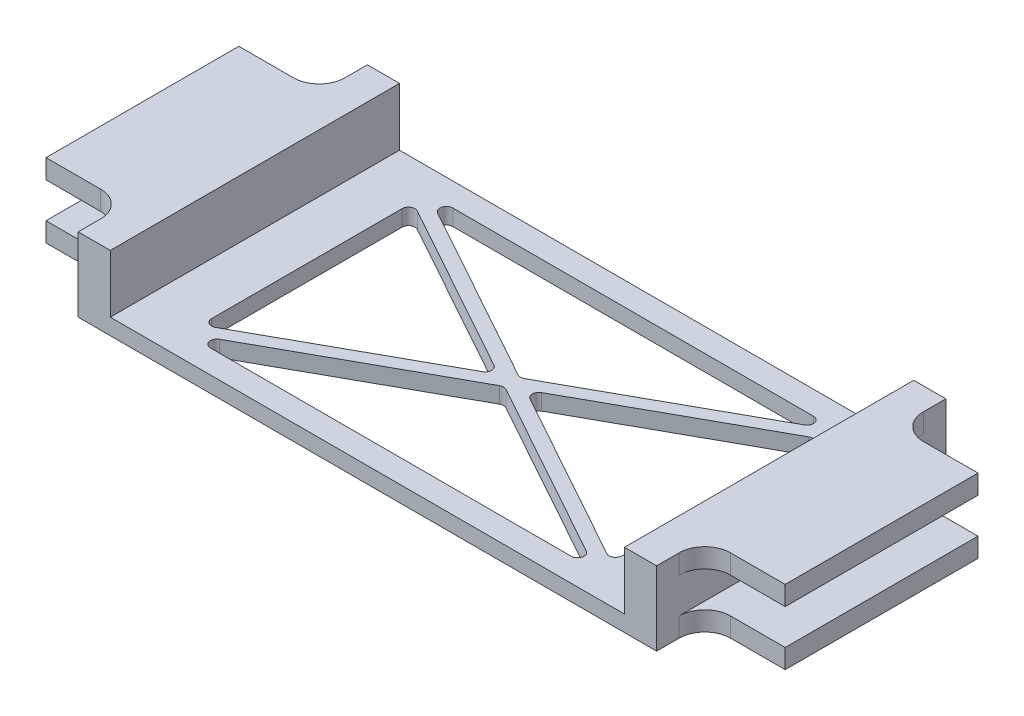
SolidWorks part; units mm, degrees
ref_plane "Front Plane" through (0, 0, 0) normal (0, 0, 1) x (1, 0, 0)
ref_plane "Top Plane" through (0, 0, 0) normal (0, 1, 0) x (1, 0, 0)
ref_plane "Right Plane" through (0, 0, 0) normal (1, 0, 0) x (0, 0, -1)
sketch "Sketch1" plane through (0, 0, 0) normal (0, 1, 0) x (1, 0, 0)
  line L1 (57.5, -15) -> (-57.5, -15)
  line L2 (57.5, -15) -> (57.5, 15)
  line L3 (57.5, 15) -> (-57.5, 15)
  line L4 (-57.5, -15) -> (-57.5, 15)
  line L5 (57.5, -15) -> (-57.5, 15) construction
  line L6 (57.5, 15) -> (-57.5, -15) construction
  line L7 (45, -22.5) -> (-45, -22.5)
  line L8 (45, -22.5) -> (45, 22.5)
  line L9 (45, 22.5) -> (-45, 22.5)
  line L10 (-45, -22.5) -> (-45, 22.5)
  line L11 (45, -22.5) -> (-45, 22.5) construction
  line L12 (45, 22.5) -> (-45, -22.5) construction
  point P0 (0, 0)
  point P6 (0, 0)
  dimension "D1" = 30
  dimension "D2" = 115
  dimension "D3" = 45
  dimension "D4" = 90
extrude "Boss-Extrude1" add sketch "Sketch1" along normal blind 11.5 contours L1 L10 L3 L4 | L10 L3 L8 L9 | L10 L1 L8 L3 | L10 L7 L8 L1 | L8 L1 L2 L3
sketch "Sketch2" plane through (0, 0, 15) normal (0, 0, 1) x (1, 0, 0)
  line L0 (-45, 11.5) -> (-45, 0) construction
  line L1 (-32.5, 3) -> (-57.5, 3)
  line L2 (-32.5, 3) -> (-32.5, 8.5)
  line L3 (-32.5, 8.5) -> (-57.5, 8.5)
  line L4 (-57.5, 3) -> (-57.5, 8.5)
  line L5 (-32.5, 3) -> (-57.5, 8.5) construction
  line L6 (-32.5, 8.5) -> (-57.5, 3) construction
  line L7 (-57.5, 11.5) -> (-57.5, 0) construction
  line L8 (-45, 11.5) -> (-57.5, 11.5) construction
  line L10 (-45, 3) -> (-45, 8.5)
  point P0 (-45, 5.75)
  line M4 (-45, 0) -> (-45, 11.5)
  line M6 (-57.5, 11.5) -> (-57.5, 0)
  dimension "D1" = 3
extrude "Cut-Extrude1" cut sketch "Sketch2" against normal through all contours L3 L1 M4 M6
mirror "Mirror1" about plane through (0, 0, 0) normal (1, 0, 0) of "Cut-Extrude1"
sketch "Sketch3" plane through (0, 0, 22.5) normal (0, 0, 1) x (1, 0, 0)
  line L0 (45, 11.5) -> (-45, 11.5) construction
  line L1 (-40, 11.5) -> (40, 11.5)
  line L2 (-40, 11.5) -> (-40, 2.5)
  line L3 (-40, 2.5) -> (40, 2.5)
  line L4 (40, 11.5) -> (40, 2.5)
  line L5 (-45, 11.5) -> (-45, 0) construction
  line L7 (45, 11.5) -> (45, 0) construction
  dimension "D1" = 5
  dimension "D2" = 5
  dimension "D3" = 9
extrude "Cut-Extrude2" cut sketch "Sketch3" against normal through all both and the other way through all
fillet "Fillet1" radius 4 8 edges at (45, 1.5, -15) (45, 10, -15) (45, 1.5, 15) (45, 10, 15) (-45, 1.5, -15) (-45, 10, -15) (-45, 1.5, 15) (-45, 10, 15)
sketch "Sketch4" plane through (0, 0, 0) normal (0, -1, 0) x (1, 0, 0)
  line L0 (45, 22.5) -> (-45, 22.5) construction
  line L1 (40, -22.5) -> (-40, -22.5)
  line L2 (40, -22.5) -> (40, 22.5)
  line L3 (40, 22.5) -> (-40, 22.5)
  line L4 (-40, -22.5) -> (-40, 22.5)
  line L5 (40, -22.5) -> (-40, 22.5) construction
  line L6 (40, 22.5) -> (-40, -22.5) construction
  line L7 (38.5007, 22.5) -> (-40, -20.9996) construction
  line L8 (38.5, -21) -> (-38.5, -21) construction
  line L9 (38.5, -21) -> (38.5, 21) construction
  line L10 (38.5, 21) -> (-38.5, 21) construction
  line L11 (-38.5, -21) -> (-38.5, 21) construction
  line L12 (38.5, -21) -> (-38.5, 21) construction
  line L13 (38.5, 21) -> (-38.5, -21) construction
  line L14 (-38.5, -22.5) -> (40, 21) construction
  line L15 (38.4722, -22.5) -> (-40, 21.0144) construction
  line L16 (-38.5, 22.5) -> (40, -21) construction
  line L17 (-31.9254, 21) -> (31.9021, 21)
  line L18 (28.5422, 16.9817) -> (0.4847, 1.4342)
  line L19 (-0.4847, 1.4342) -> (-28.5417, 16.9817)
  line L20 (30.4694, 15.7187) -> (3.6819, 0.8747)
  line L21 (3.6819, -0.8747) -> (30.4422, -15.7036)
  line L22 (28.0576, 18.8564) -> (-28.057, 18.8564)
  line L23 (-3.6819, -0.8747) -> (-30.4407, -15.7028)
  line L24 (-28.0576, -18.8567) -> (28.0367, -18.8567)
  line L25 (-30.4407, 15.7028) -> (-3.6819, 0.8747)
  line L26 (-31.9254, -21) -> (31.9021, -21)
  line L27 (28.5216, -16.9822) -> (0.4841, -1.4348)
  line L28 (-0.4856, -1.4347) -> (-28.5423, -16.982)
  line L29 (-31.9254, 21) -> (-31.9254, -21) construction
  line L30 (31.9021, 21) -> (31.9021, -21) construction
  line L31 (31.9541, 14.8431) -> (31.9269, -14.8299)
  line L32 (-31.9254, 14.8281) -> (-31.9254, -14.8281)
  arc A0 (-0.4856, -1.4347) -> (0.4841, -1.4348) centre (-0.0009, -2.3094) cw
  arc A1 (-28.5423, -16.982) -> (-28.0576, -18.8567) centre (-28.0576, -17.8567) ccw
  arc A2 (28.5216, -16.9822) -> (28.0367, -18.8567) centre (28.0367, -17.8567) cw
  arc A3 (28.0576, 18.8564) -> (28.5422, 16.9817) centre (28.0576, 17.8564) cw
  arc A4 (3.6819, -0.8747) -> (3.6819, 0.8747) centre (4.1666, 0) cw
  arc A5 (-28.057, 18.8564) -> (-28.5417, 16.9817) centre (-28.057, 17.8564) ccw
  arc A6 (-3.6819, -0.8747) -> (-3.6819, 0.8747) centre (-4.1666, 0) ccw
  arc A11 (0.4847, 1.4342) -> (-0.4847, 1.4342) centre (0, 2.3089) cw
  arc A12 (-30.4407, 15.7028) -> (-31.9254, 14.8281) centre (-30.9254, 14.8281) ccw
  arc A13 (-30.4407, -15.7028) -> (-31.9254, -14.8281) centre (-30.9254, -14.8281) cw
  arc A14 (31.9541, 14.8431) -> (30.4694, 15.7187) centre (30.9541, 14.844) ccw
  arc A15 (30.4422, -15.7036) -> (31.9269, -14.8299) centre (30.9269, -14.829) ccw
  point P0 (0, 0)
  point P8 (0, 0)
  point P21 (-31.9896, 18.9218)
  point P22 (32.0873, 18.9689)
  point P29 (-31.9477, -18.8949)
  point P31 (31.9958, -18.9193)
  point P36 (-0.0007, -1.166)
  point P40 (35.7672, -21)
  point P43 (38.5, -20.1688)
  point P46 (2.1034, 0)
  point P49 (38.5, 20.1688)
  point P52 (-2.1034, 0)
  point P55 (-38.5, 20.1826)
  point P58 (-38.5002, -20.1685)
  point P61 (-35.7931, 21)
  point P64 (35.7938, 21)
  point P67 (0, 1.1656)
  dimension "D4" = 1
  dimension "D5" = 1
  dimension "D6" = 1
  dimension "D7" = 1
  dimension "D8" = 1
  dimension "D1" = 80
  dimension "D2" = 1.5
  dimension "D3" = 1.5
extrude "Cut-Extrude4" cut sketch "Sketch4" against normal blind 10
